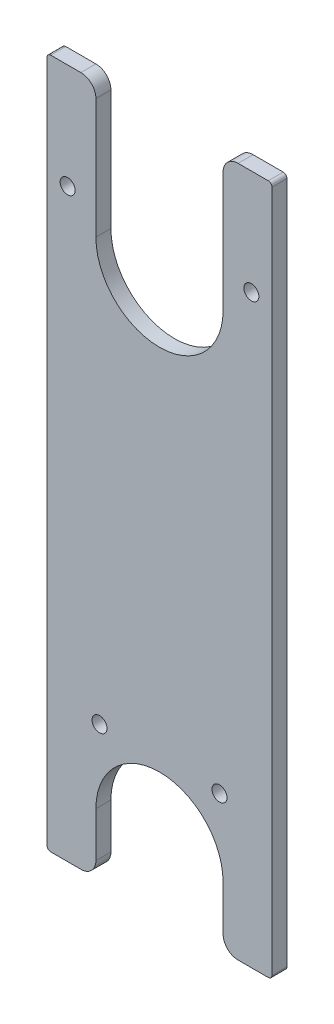
SolidWorks part; units mm, degrees
material "PC High Viscosity"
ref_plane "Front Plane" through (0, 0, 0) normal (0, 0, 1) x (1, 0, 0)
ref_plane "Top Plane" through (0, 0, 0) normal (0, 1, 0) x (1, 0, 0)
ref_plane "Right Plane" through (0, 0, 0) normal (1, 0, 0) x (0, 0, -1)
sketch "Sketch2" plane through (0, 0, 0) normal (0, 0, 1) x (1, 0, 0)
  line L0 (-47.625, -279.4) -> (-26.924, -279.4)
  line L1 (-26.924, -279.4) -> (-26.924, -254)
  line L2 (-47.625, -279.4) -> (-47.625, 12.7)
  line L3 (-47.625, 12.7) -> (-26.924, 12.7)
  line L4 (-26.924, 12.7) -> (-26.924, -44.45)
  line L5 (0, 0) -> (0, -254) construction
  line L6 (47.625, 12.7) -> (26.924, 12.7)
  line L7 (26.924, -279.4) -> (26.924, -254)
  line L8 (47.625, -279.4) -> (26.924, -279.4)
  line L9 (26.924, 12.7) -> (26.924, -44.45)
  line L10 (47.625, -279.4) -> (47.625, 12.7)
  circle A0 centre (0, 0) radius 25.4 construction
  circle A1 centre (0, -254) radius 25.4 construction
  arc A2 (-26.924, -254) -> (26.924, -254) centre (0, -254) cw
  arc A3 (-26.924, -44.45) -> (26.924, -44.45) centre (0, -44.45) ccw
  dimension "D2" = 50.8
  dimension "D3" = 26.924
  dimension "D1" = 254
  dimension "D4" = 22.225
  dimension "D5" = 44.45
  dimension "D6" = 12.7
extrude "Boss-Extrude1" add sketch "Sketch2" along normal blind 6.35
fillet "Fillet1" radius 6.35 4 edges at (26.924, -279.4, 3.175) (-26.924, -279.4, 3.175) (26.924, 12.7, 3.175) (-26.924, 12.7, 3.175)
fillet "Fillet2" radius 1.5875 4 edges at (-47.625, 12.7, 3.175) (47.625, 12.7, 3.175) (47.625, -279.4, 3.175) (-47.625, -279.4, 3.175)
hole_wizard "1/4 (0.25) Diameter Hole1" positions "Sketch4" profile "Sketch5" hole size "1/4" standard "ANSI Inch" end condition through all
sketch "Sketch4" plane through (0, 0, 6.35) normal (0, 0, 1) x (1, 0, 0)
  line L0 (0, 0) -> (0, -227.076) construction
  line L1 (-46.0375, -279.4) -> (-33.274, -279.4) construction
  arc A0 (26.924, -254) -> (-26.924, -254) centre (0, -254) ccw construction
  point P0 (-25.4, -222.25)
  point P2 (-38.8938, -31.75)
  point P12 (38.8938, -31.75)
  point P13 (25.4, -222.25)
  dimension "D1" = 77.7875
  dimension "D2" = 57.15
  dimension "D3" = 247.65
  dimension "D4" = 50.8
sketch "Sketch5" plane through (-25.4, -222.25, 6.35) normal (1, 0, 0) x (0, -1, 0)
  line L0 (0, 0) -> (0, 6.35)
  line L1 (0, 6.35) -> (3.175, 6.35)
  line L2 (3.175, 6.35) -> (3.175, 0)
  line L5 (3.175, 0) -> (0, 0)
  line L11 (0, -6.35) -> (0, 107.95) construction
  dimension "Thru Hole Dia." = 6.35
  dimension "Thru Hole Depth" = 6.35
